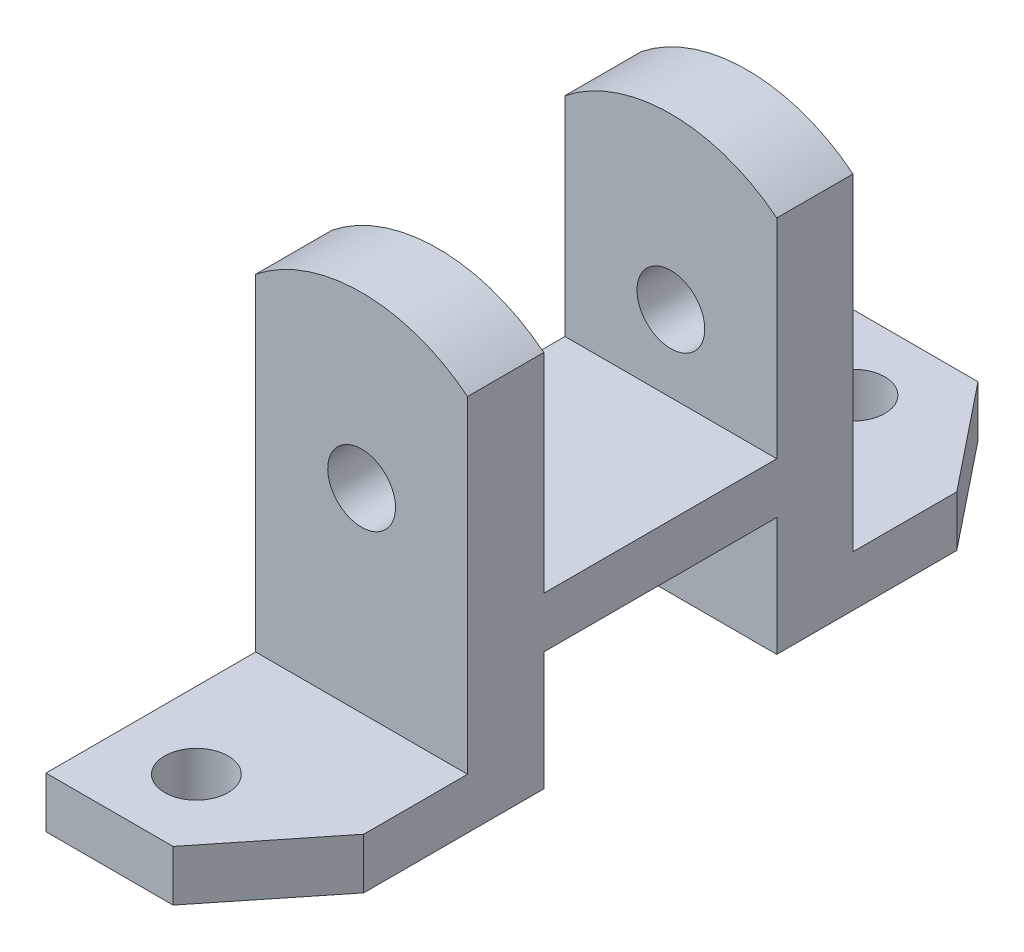
SolidWorks part; units mm, degrees
ref_plane "Front Plane" through (0, 0, 0) normal (0, 0, 1) x (1, 0, 0)
ref_plane "Top Plane" through (0, 0, 0) normal (0, 1, 0) x (1, 0, 0)
ref_plane "Right Plane" through (0, 0, 0) normal (1, 0, 0) x (0, 0, -1)
sketch "Sketch1" plane through (0, 0, 0) normal (1, 0, 0) x (0, 0, -1)
  line L0 (-95, -40) -> (-27.5, -40)
  line L1 (0, 86.1739) -> (0, -69.4644) construction
  line L2 (95, -40) -> (95, -28)
  line L3 (-95, -40) -> (-95, -28)
  line L4 (95, -28) -> (45.5, -28)
  line L5 (-95, -28) -> (-45.5, -28)
  line L6 (45.5, -28) -> (45.5, 58)
  line L7 (-45.5, -28) -> (-45.5, 58)
  line L8 (45.5, 58) -> (27.5, 58)
  line L9 (-45.5, 58) -> (-27.5, 58)
  line L10 (27.5, 58) -> (27.5, 0)
  line L11 (-27.5, 58) -> (-27.5, 0)
  line L12 (-27.5, 0) -> (27.5, 0)
  line L13 (-27.5, -40) -> (-27.5, -12)
  line L14 (-27.5, -12) -> (27.5, -12)
  line L15 (27.5, -12) -> (27.5, -40)
  line L16 (27.5, -40) -> (95, -40)
  point P4 (0, -12)
  point P17 (0, 0)
  point P21 (0, -12)
  dimension "D1" = 190
  dimension "D2" = 12
  dimension "D3" = 12
  dimension "D4" = 55
  dimension "D5" = 18
  dimension "D6" = 58
  dimension "D7" = 28
extrude "Boss-Extrude1" add sketch "Sketch1" along normal mid plane 50
chamfer "Chamfer1" distance 20 distance2 25 2 edges at (25, -34, 95) (25, -34, -95)
sketch "Sketch2" plane through (0, 0, -45.5) normal (0, 0, -1) x (-1, 0, 0)
  line L2 (-25, 58) -> (25, 58) construction
  line L3 (-25, -28) -> (-25, 58) construction
  line L4 (25, -28) -> (25, 58) construction
  line L5 (-25, 58) -> (25, 58)
  line L6 (25, 49.225) -> (25, 58)
  line L7 (-25, 49.225) -> (-25, 58)
  circle A0 centre (0, 18) radius 8
  arc A1 (-25, 49.225) -> (25, 49.225) centre (0, 18) cw
  point P2 (40, 47.6608)
  point P6 (-38.7045, 51.9782)
  point P8 (-28.9268, 66.2002)
  point P10 (0, 0)
  point P13 (0, 0)
  line M2 (25, -28) -> (25, 58)
  line M3 (25, 58) -> (-25, 58)
  line M4 (-25, 58) -> (-25, -28)
  dimension "D1" = 16
  dimension "D2" = 40
extrude "Cut-Extrude1" cut sketch "Sketch2" against normal through all both and the other way through all contours A0 | A1 L5 M4 | A1 M3 M2
sketch "Sketch4" plane through (0, -28, 0) normal (0, 1, 0) x (1, 0, 0)
  line L0 (-7, -77.5) -> (-7, 77.5) construction
  line L1 (-25, 95) -> (-25, 45.5) construction
  circle A0 centre (-7, -77.5) radius 7.5
  circle A1 centre (-7, 77.5) radius 7.5
  point P3 (-7, 0)
  dimension "D3" = 15
  dimension "D1" = 155
  dimension "D2" = 18
extrude "Cut-Extrude2" cut sketch "Sketch4" against normal through all
sketch "Sketch6" plane through (0, -40, 0) normal (0, -1, 0) x (1, 0, 0)
  line L0 (-7, 27.5) -> (-7, -27.5) construction
  line L3 (25, 27.5) -> (-25, 27.5) construction
  line L4 (25, -27.5) -> (-25, -27.5) construction
  line L6 (-11, -27.5) -> (-3, -27.5)
  line L7 (-11, -27.5) -> (-11, 27.5)
  line L8 (-11, 27.5) -> (-3, 27.5)
  line L9 (-3, -27.5) -> (-3, 27.5)
  line L10 (-11, -27.5) -> (-3, 27.5) construction
  line L11 (-11, 27.5) -> (-3, -27.5) construction
  point P1 (-7, 0)
  point P6 (-7, 0)
  point P10 (-7, -77.5)
  dimension "D1" = 8
extrude "Boss-Extrude2" add sketch "Sketch6" against normal up to surface (28 mm away) up to face at (0, -12, 0)
